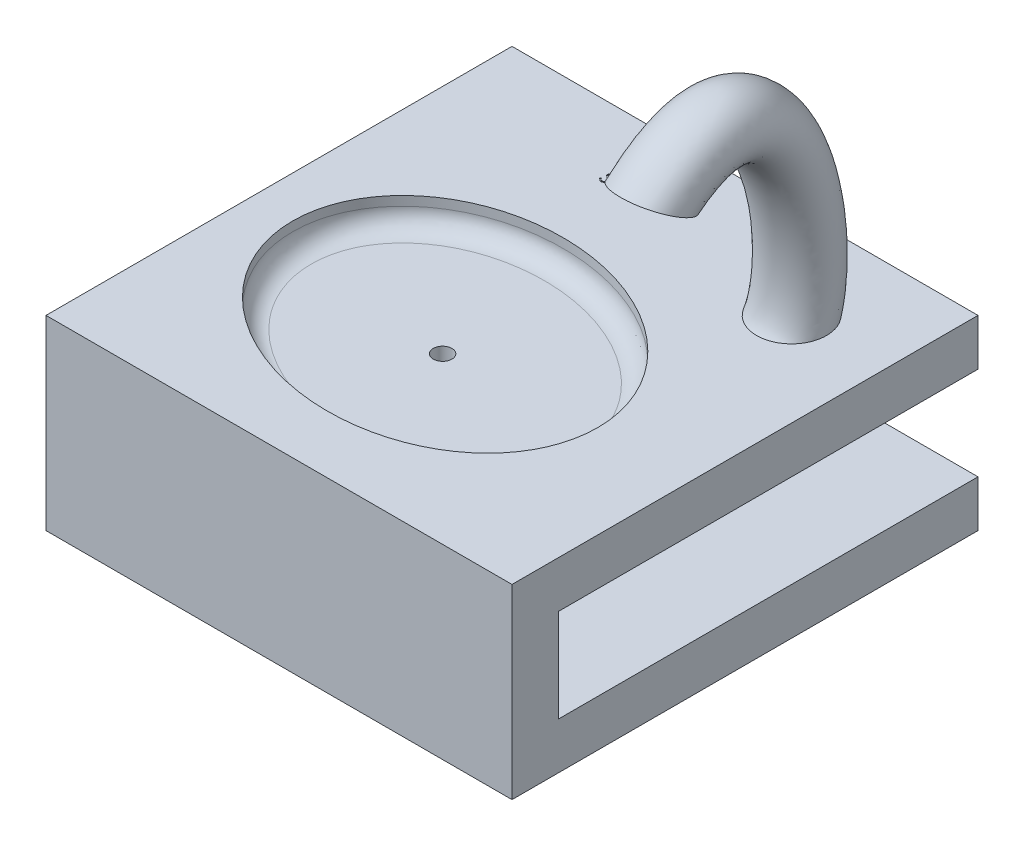
SolidWorks part; units mm, degrees
material "Ceramic Porcelain"
ref_plane "Front Plane" through (0, 0, 0) normal (0, 0, 1) x (1, 0, 0)
ref_plane "Top Plane" through (0, 0, 0) normal (0, 1, 0) x (1, 0, 0)
ref_plane "Right Plane" through (0, 0, 0) normal (1, 0, 0) x (0, 0, -1)
sketch "Sketch1" plane through (0, 0, 0) normal (0, 1, 0) x (1, 0, 0)
  line L1 (-63.5, 63.5) -> (63.5, 63.5)
  line L2 (-63.5, 63.5) -> (-63.5, -63.5)
  line L3 (-63.5, -63.5) -> (63.5, -63.5)
  line L4 (63.5, 63.5) -> (63.5, -63.5)
  line L5 (-63.5, 63.5) -> (63.5, -63.5) construction
  line L6 (-63.5, -63.5) -> (63.5, 63.5) construction
  point P0 (0, 0)
  dimension "D1" = 127
  dimension "D2" = 127
extrude "Boss-Extrude1" add sketch "Sketch1" along normal blind 50.8
sketch "Sketch2" plane through (63.5, 0, 0) normal (1, 0, 0) x (0, 0, -1)
  line L0 (63.5, 50.8) -> (63.5, 0) construction
  line L1 (63.5, 38.1) -> (-50.8, 38.1)
  line L2 (63.5, 38.1) -> (63.5, 12.7)
  line L3 (63.5, 12.7) -> (-50.8, 12.7)
  line L4 (-50.8, 38.1) -> (-50.8, 12.7)
  line L5 (-63.5, 50.8) -> (63.5, 50.8) construction
  line L6 (-63.5, 0) -> (63.5, 0) construction
  line L7 (-63.5, 50.8) -> (-63.5, 0) construction
  dimension "D1" = 12.7
  dimension "D2" = 12.7
  dimension "D3" = 12.7
extrude "Cut-Extrude1" cut sketch "Sketch2" against normal blind 114.3
sketch "Sketch3" plane through (0, 50.8, 0) normal (0, 1, 0) x (1, 0, 0)
  line L0 (63.5, 63.5) -> (-63.5, 63.5) construction
  line L1 (63.5, -63.5) -> (63.5, 63.5) construction
  circle A0 centre (38.1, 38.1) radius 9.525
  dimension "D1" = 19.05
  dimension "D2" = 25.4
  dimension "D3" = 25.4
ref_plane "Plane1" through (38.1, 0, 0) normal (1, 0, 0) x (0, 0, -1)
sketch "Sketch4" plane through (38.1, 0, 0) normal (1, 0, 0) x (0, 0, -1)
  line L0 (47.625, 50.8) -> (28.575, 50.8) construction
  line L1 (-63.5, 50.8) -> (63.5, 50.8) construction
  line L4 (63.5, 50.8) -> (-63.5, 50.8) construction
  spline S0 degree 3 poles (38.1, 50.8) (45.6647, 68.7647) (33.8219, 126.4157) (0, 97.6454) knots 0 0 0 0 1 1 1 1
  dimension "D1" = 84.7978
  dimension "D3" = 39.5238
  dimension "D2" = 46.8454
  dimension "D4" = 60.383
  dimension "D5" = 17.944
  dimension "D6" = 51.7681
surface "Surface-Sweep1"
sketch "Sketch8" plane through (0, 50.8, 0) normal (0, 1, 0) x (1, 0, 0)
  ellipse E0 centre (-7.0007, -11.2183) end of major axis (-51.5176, -1.4806) minor radius 36.051
extrude "Cut-Extrude2" cut sketch "Sketch8" against normal blind 7.62 contours E0
fillet "Fillet1" radius 5.08 1 edges at (-51.5176, 43.18, 1.4806)
sketch "Sketch9" plane through (0, 50.8, 0) normal (0, 1, 0) x (1, 0, 0)
  text T0 "SINK"
extrude "Cut-Extrude3" cut sketch "Sketch9" against normal blind 0.254
sketch "Sketch10" plane through (0, 43.18, 0) normal (0, 1, 0) x (1, 0, 0)
  line L0 (63.5, 63.5) -> (-63.5, 63.5) construction
  line L1 (63.5, -63.5) -> (63.5, 63.5) construction
  circle A0 centre (-8.0146, -10.8916) radius 2.54
  dimension "D1" = 5.08
  dimension "D2" = 74.3916
  dimension "D3" = 71.5146
extrude "Cut-Extrude4" cut sketch "Sketch10" against normal up to surface (5.08 mm away) up to face at (6.35, 38.1, -6.35)
sketch "Sketch11" plane through (-50.8, 0, 0) normal (1, 0, 0) x (0, 0, -1)
  line L0 (-50.8, 22.2854) -> (-28.9831, 12.7)
  line L1 (-50.8, 38.1) -> (-50.8, 12.7) construction
  line L2 (-50.8, 12.7) -> (63.5, 12.7) construction
rib "Rib1" sketch "Sketch11" sketch "Sketch11" thickness 2.54 extrusion direction parallel to sketch draft on no parameters "D1"=2.54
